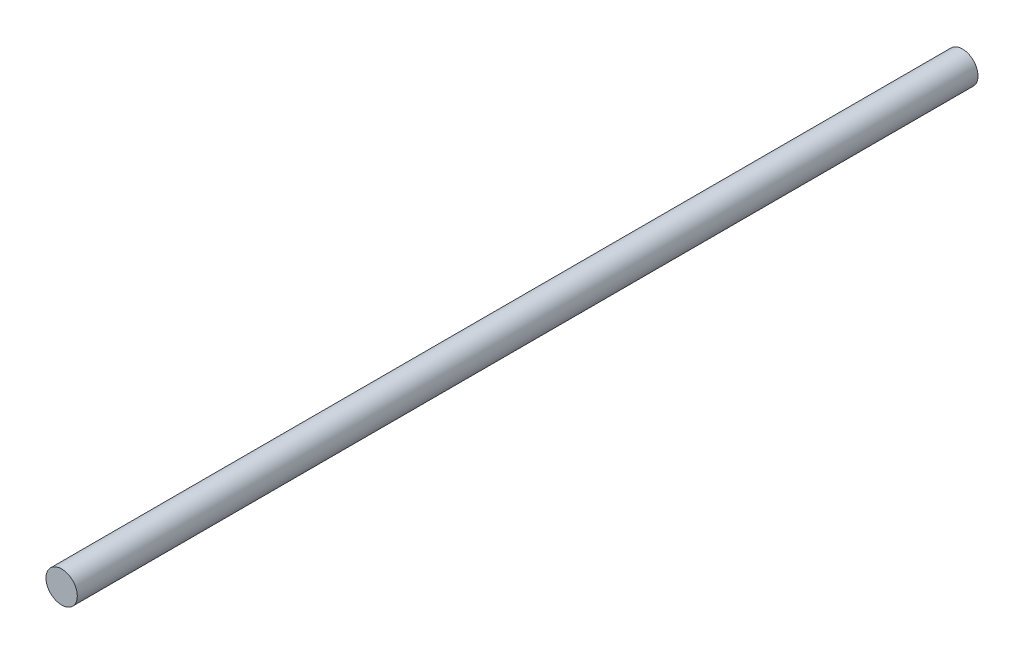
SolidWorks part; units mm, degrees
ref_plane "前视基准面" through (0, 0, 0) normal (0, 0, 1) x (1, 0, 0)
ref_plane "上视基准面" through (0, 0, 0) normal (0, 1, 0) x (1, 0, 0)
ref_plane "右视基准面" through (0, 0, 0) normal (1, 0, 0) x (0, 0, -1)
sketch "草图1" plane through (0, 0, 0) normal (0, 0, 1) x (1, 0, 0)
  circle A0 centre (0, 0) radius 4
extrude "凸台-拉伸1" add sketch "草图1" along normal mid plane 230
